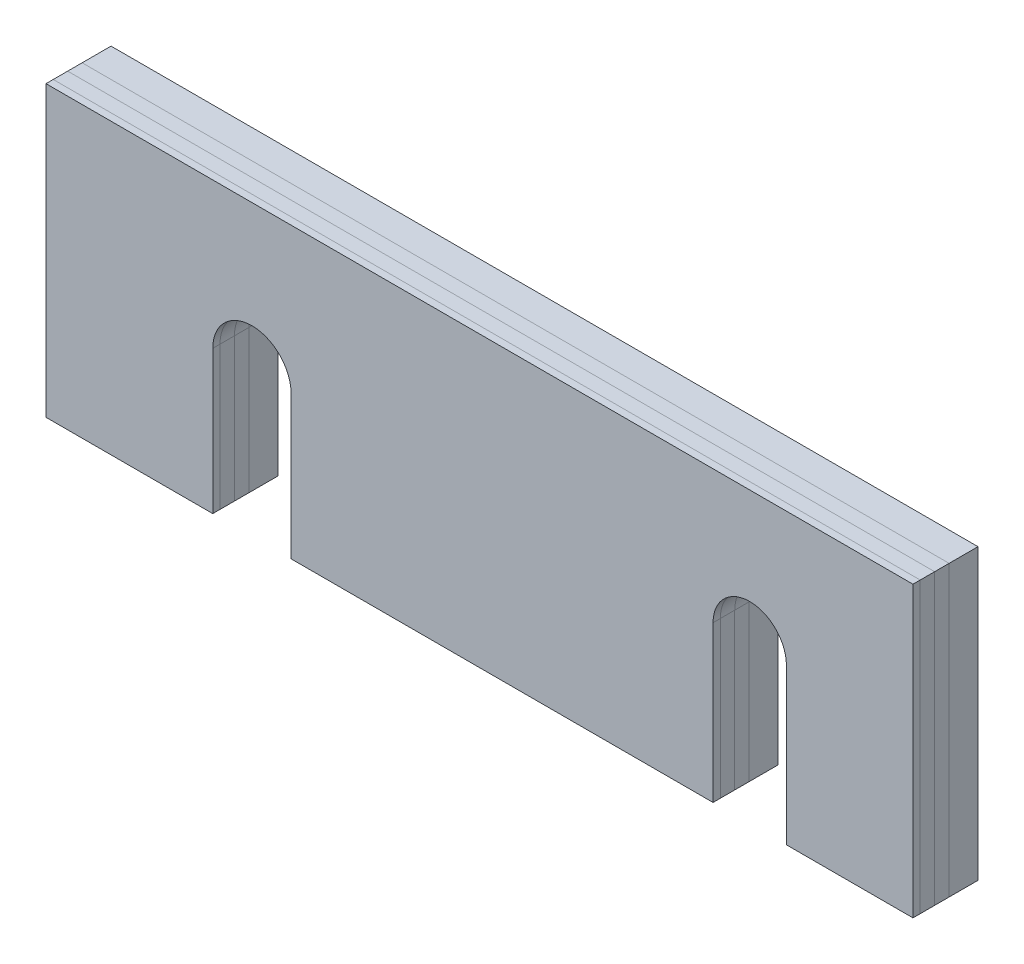
SolidWorks part; units mm, degrees
material "AISI 304"
ref_plane "Front Plane" through (0, 0, 0) normal (0, 0, 1) x (1, 0, 0)
ref_plane "Top Plane" through (0, 0, 0) normal (0, 1, 0) x (1, 0, 0)
ref_plane "Right Plane" through (0, 0, 0) normal (1, 0, 0) x (0, 0, -1)
sketch "Sketch1" plane through (0, 0, 0) normal (0, 0, 1) x (1, 0, 0)
  line L0 (-13.0359, -3.7254) -> (-13.0359, 6.2746)
  line L1 (-13.0359, 6.2746) -> (16.9641, 6.2746)
  line L2 (16.9641, 6.2746) -> (16.9641, -3.7254)
  line L3 (16.9641, -3.7254) -> (12.584, -3.7254)
  line L4 (12.584, -3.7254) -> (12.584, 1.6628)
  line L5 (10.0463, 1.6628) -> (10.0463, -3.7254)
  line L6 (10.0463, -3.7254) -> (-4.5539, -3.7254)
  line L7 (-4.5539, -3.7254) -> (-4.5539, 1.2283)
  line L8 (-7.2654, 1.2283) -> (-7.2654, -3.7254)
  line L9 (-7.2654, -3.7254) -> (-13.0359, -3.7254)
  arc A0 (12.584, 1.6628) -> (10.0463, 1.6628) centre (11.3152, 1.6628) ccw
  arc A1 (-4.5539, 1.2283) -> (-7.2654, 1.2283) centre (-5.9096, 1.2283) ccw
  dimension "D1" = 30
  dimension "D2" = 10
extrude "Boss-Extrude1" add sketch "Sketch1" along normal blind 1
sketch "Sketch2" plane through (0, 0, 1) normal (0, 0, 1) x (1, 0, 0)
  line L10 (-13.0359, -3.7254) -> (-7.2654, -3.7254)
  line L11 (-7.2654, -3.7254) -> (-7.2654, 1.2283)
  line L12 (-4.5539, 1.2283) -> (-4.5539, -3.7254)
  line L13 (-4.5539, -3.7254) -> (10.0463, -3.7254)
  line L14 (10.0463, -3.7254) -> (10.0463, 1.6628)
  line L15 (12.584, 1.6628) -> (12.584, -3.7254)
  line L16 (12.584, -3.7254) -> (16.9641, -3.7254)
  line L17 (16.9641, -3.7254) -> (16.9641, 6.2746)
  line L18 (16.9641, 6.2746) -> (-13.0359, 6.2746)
  line L19 (-13.0359, 6.2746) -> (-13.0359, -3.7254)
  line L20 (-13.0359, -3.7254) -> (-7.2654, -3.7254)
  line L21 (-7.2654, -3.7254) -> (-7.2654, 1.2283)
  line L22 (-4.5539, 1.2283) -> (-4.5539, -3.7254)
  line L23 (-4.5539, -3.7254) -> (10.0463, -3.7254)
  line L24 (10.0463, -3.7254) -> (10.0463, 1.6628)
  line L25 (12.584, 1.6628) -> (12.584, -3.7254)
  line L26 (12.584, -3.7254) -> (16.9641, -3.7254)
  line L27 (16.9641, -3.7254) -> (16.9641, 6.2746)
  line L28 (16.9641, 6.2746) -> (-13.0359, 6.2746)
  line L29 (-13.0359, 6.2746) -> (-13.0359, -3.7254)
  arc A2 (-4.5539, 1.2283) -> (-7.2654, 1.2283) centre (-5.9096, 1.2283) ccw
  arc A3 (12.584, 1.6628) -> (10.0463, 1.6628) centre (11.3152, 1.6628) ccw
  arc A4 (-4.5539, 1.2283) -> (-7.2654, 1.2283) centre (-5.9096, 1.2283) ccw
  arc A5 (12.584, 1.6628) -> (10.0463, 1.6628) centre (11.3152, 1.6628) ccw
  dimension "D1" = 0
extrude "Boss-Extrude2" add sketch "Sketch2" along normal blind 0.5 separate body
sketch "Sketch3" plane through (0, 0, 1.5) normal (0, 0, 1) x (1, 0, 0)
  line L10 (-13.0359, 6.2746) -> (-13.0359, -3.7254)
  line L11 (-13.0359, -3.7254) -> (-7.2654, -3.7254)
  line L12 (-7.2654, -3.7254) -> (-7.2654, 1.2283)
  line L13 (-4.5539, 1.2283) -> (-4.5539, -3.7254)
  line L14 (-4.5539, -3.7254) -> (10.0463, -3.7254)
  line L15 (10.0463, -3.7254) -> (10.0463, 1.6628)
  line L16 (12.584, 1.6628) -> (12.584, -3.7254)
  line L17 (12.584, -3.7254) -> (16.9641, -3.7254)
  line L18 (16.9641, -3.7254) -> (16.9641, 6.2746)
  line L19 (16.9641, 6.2746) -> (-13.0359, 6.2746)
  line L20 (-13.0359, 6.2746) -> (-13.0359, -3.7254)
  line L21 (-13.0359, -3.7254) -> (-7.2654, -3.7254)
  line L22 (-7.2654, -3.7254) -> (-7.2654, 1.2283)
  line L23 (-4.5539, 1.2283) -> (-4.5539, -3.7254)
  line L24 (-4.5539, -3.7254) -> (10.0463, -3.7254)
  line L25 (10.0463, -3.7254) -> (10.0463, 1.6628)
  line L26 (12.584, 1.6628) -> (12.584, -3.7254)
  line L27 (12.584, -3.7254) -> (16.9641, -3.7254)
  line L28 (16.9641, -3.7254) -> (16.9641, 6.2746)
  line L29 (16.9641, 6.2746) -> (-13.0359, 6.2746)
  arc A2 (-4.5539, 1.2283) -> (-7.2654, 1.2283) centre (-5.9096, 1.2283) ccw
  arc A3 (12.584, 1.6628) -> (10.0463, 1.6628) centre (11.3152, 1.6628) ccw
  arc A4 (-4.5539, 1.2283) -> (-7.2654, 1.2283) centre (-5.9096, 1.2283) ccw
  arc A5 (12.584, 1.6628) -> (10.0463, 1.6628) centre (11.3152, 1.6628) ccw
  dimension "D1" = 0
extrude "Boss-Extrude3" add sketch "Sketch3" along normal blind 0.5 separate body
sketch "Sketch4" plane through (0, 0, 2) normal (0, 0, 1) x (1, 0, 0)
  line L10 (16.9641, 6.2746) -> (-13.0359, 6.2746)
  line L11 (-13.0359, 6.2746) -> (-13.0359, -3.7254)
  line L12 (-13.0359, -3.7254) -> (-7.2654, -3.7254)
  line L13 (-7.2654, -3.7254) -> (-7.2654, 1.2283)
  line L14 (-4.5539, 1.2283) -> (-4.5539, -3.7254)
  line L15 (-4.5539, -3.7254) -> (10.0463, -3.7254)
  line L16 (10.0463, -3.7254) -> (10.0463, 1.6628)
  line L17 (12.584, 1.6628) -> (12.584, -3.7254)
  line L18 (12.584, -3.7254) -> (16.9641, -3.7254)
  line L19 (16.9641, -3.7254) -> (16.9641, 6.2746)
  line L20 (16.9641, 6.2746) -> (-13.0359, 6.2746)
  line L21 (-13.0359, 6.2746) -> (-13.0359, -3.7254)
  line L22 (-13.0359, -3.7254) -> (-7.2654, -3.7254)
  line L23 (-7.2654, -3.7254) -> (-7.2654, 1.2283)
  line L24 (-4.5539, 1.2283) -> (-4.5539, -3.7254)
  line L25 (-4.5539, -3.7254) -> (10.0463, -3.7254)
  line L26 (10.0463, -3.7254) -> (10.0463, 1.6628)
  line L27 (12.584, 1.6628) -> (12.584, -3.7254)
  line L28 (12.584, -3.7254) -> (16.9641, -3.7254)
  line L29 (16.9641, -3.7254) -> (16.9641, 6.2746)
  arc A2 (-4.5539, 1.2283) -> (-7.2654, 1.2283) centre (-5.9096, 1.2283) ccw
  arc A3 (12.584, 1.6628) -> (10.0463, 1.6628) centre (11.3152, 1.6628) ccw
  arc A4 (-4.5539, 1.2283) -> (-7.2654, 1.2283) centre (-5.9096, 1.2283) ccw
  arc A5 (12.584, 1.6628) -> (10.0463, 1.6628) centre (11.3152, 1.6628) ccw
  dimension "D1" = 0
extrude "Boss-Extrude4" add sketch "Sketch4" along normal blind 0.25 separate body
